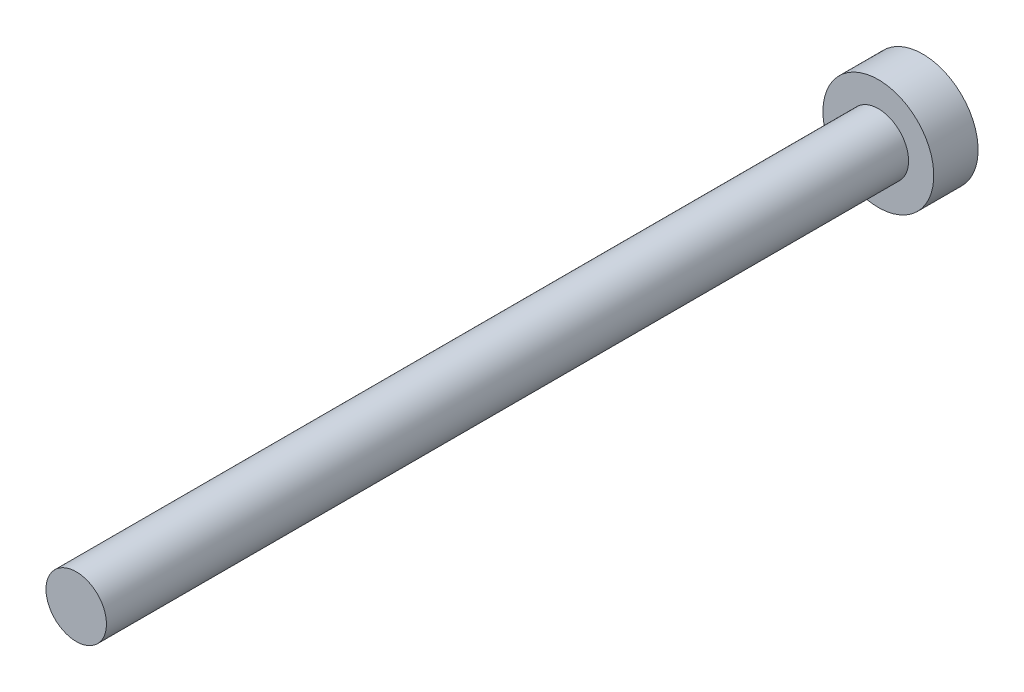
SolidWorks part; units mm, degrees
ref_plane "Front Plane" through (0, 0, 0) normal (0, 0, 1) x (1, 0, 0)
ref_plane "Top Plane" through (0, 0, 0) normal (0, 1, 0) x (1, 0, 0)
ref_plane "Right Plane" through (0, 0, 0) normal (1, 0, 0) x (0, 0, -1)
sketch "Sketch1" plane through (0, 0, 0) normal (0, 0, 1) x (1, 0, 0)
  circle A0 centre (0, 0) radius 1.5
  dimension "D1" = 3
extrude "Boss-Extrude1" add sketch "Sketch1" along normal blind 42
sketch "Sketch2" plane through (0, 0, 0) normal (0, 0, -1) x (-1, 0, 0)
  circle A0 centre (0, 0) radius 2.75
  dimension "D1" = 5.5
extrude "Boss-Extrude2" add sketch "Sketch2" against normal blind 2.2
